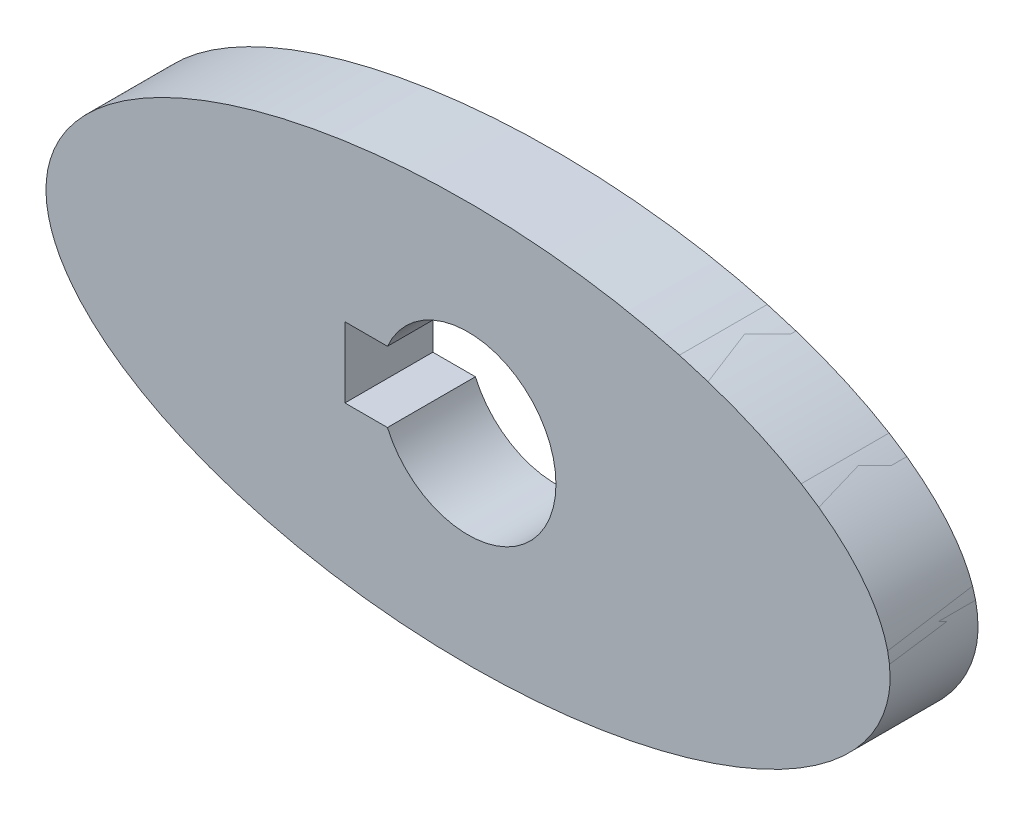
SolidWorks part; units mm, degrees
ref_plane "Alzado" through (0, 0, 0) normal (0, 0, 1) x (1, 0, 0)
ref_plane "Planta" through (0, 0, 0) normal (0, 1, 0) x (1, 0, 0)
ref_plane "Vista lateral" through (0, 0, 0) normal (1, 0, 0) x (0, 0, -1)
sketch "Croquis1" plane through (0, 0, 0) normal (0, 0, 1) x (1, 0, 0)
  line L1 (-7, 2) -> (-4.5826, 2)
  line L2 (-7, 2) -> (-7, -2)
  line L3 (-7, -2) -> (-4.5826, -2)
  arc A0 (-4.5826, -2) -> (-4.5826, 2) centre (0, 0) ccw
  ellipse E0 centre (0, 0) end of major axis (24, 0) minor radius 11.3936
  point P3 (-7, 0)
  dimension "D2" = 10
  dimension "D1" = 48
  dimension "D3" = 7
  dimension "D4" = 4
extrude "Saliente-Extruir1" add sketch "Croquis1" along normal blind 5
sketch "Croquis2" plane through (0, 0, 5) normal (0, 0, 1) x (1, 0, 0)
  ellipse E0 centre (0, 0) end of major axis (24, 0) minor radius 11.3936 construction
  ellipse E1 centre (0, 0) end of major axis (24, 0) minor radius 11.3936
surface "Superficie-Extruir1" sketch "Croquis2" parameters "D1"=5
